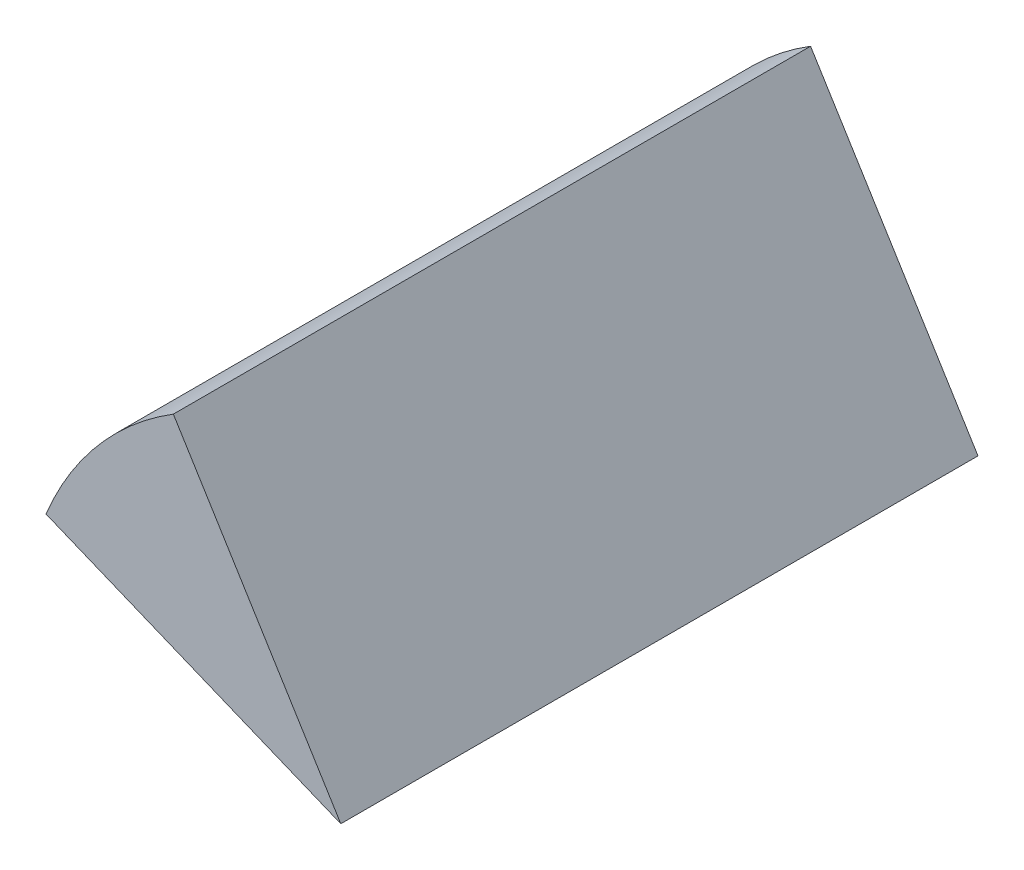
SolidWorks part; units mm, degrees
ref_plane "Alzado" through (0, 0, 0) normal (0, 0, 1) x (1, 0, 0)
ref_plane "Planta" through (0, 0, 0) normal (0, 1, 0) x (1, 0, 0)
ref_plane "Vista lateral" through (0, 0, 0) normal (1, 0, 0) x (0, 0, -1)
sketch "Croquis1" plane through (0, 0, 0) normal (0, 0, 1) x (1, 0, 0)
  line L1 (0, 0) -> (-13.1376, 21.2698)
  line L2 (0, 0) -> (-23.1306, 9.4856)
  arc A0 (-13.1376, 21.2698) -> (-23.1306, 9.4856) centre (0, 0) ccw
  dimension "D1" = 50
  dimension "D2" = 36
extrude "Saliente-Extruir1" add sketch "Croquis1" along normal blind 50
sketch "Croquis2" plane through (0, 0, 0) normal (0, 0, -1) x (-1, 0, 0)
  circle A0 centre (14.381, 12.1722) radius 5
  dimension "D1" = 10
extrude "Cortar-Extruir1" cut sketch "Croquis2" against normal blind 10
